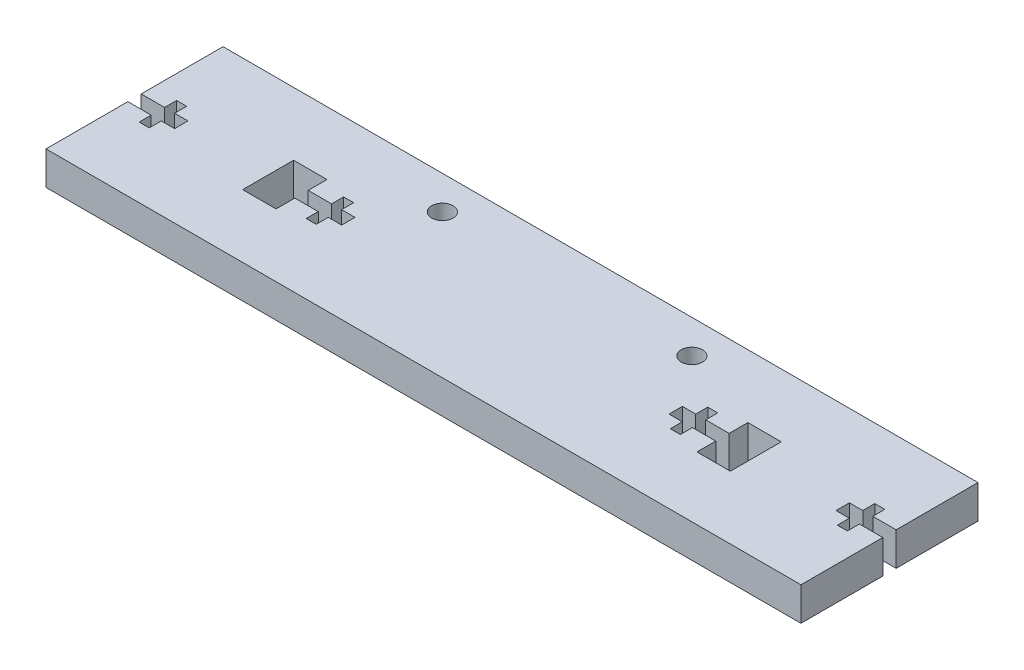
SolidWorks part; units mm, degrees
material "Acrílico (médio-alto impacto)"
ref_plane "Plano frontal" through (0, 0, 0) normal (0, 0, 1) x (1, 0, 0)
ref_plane "Plano superior" through (0, 0, 0) normal (0, 1, 0) x (1, 0, 0)
ref_plane "Plano direito" through (0, 0, 0) normal (1, 0, 0) x (0, 0, -1)
sketch "Esboço1" plane through (0, 0, 0) normal (0, 1, 0) x (1, 0, 0)
  line L1 (-76.7364, -5.6593) -> (36.2636, -5.6593)
  line L2 (-76.7364, -5.6593) -> (-76.7364, -32.1593)
  line L3 (-76.7364, -32.1593) -> (36.2636, -32.1593)
  line L4 (36.2636, -5.6593) -> (36.2636, -32.1593)
extrude "Ressalto-extrusão1" add sketch "Esboço1" along normal blind 5
sketch "Esboço2" plane through (0, 5, 0) normal (0, 1, 0) x (1, 0, 0)
  line L0 (36.2636, -32.1593) -> (36.2636, -5.6593) construction
  line L1 (16.2636, -15.1043) -> (11.2636, -15.1043)
  line L2 (16.2636, -15.1043) -> (16.2636, -22.7243)
  line L3 (16.2636, -22.7243) -> (11.2636, -22.7243)
  line L4 (11.2636, -15.1043) -> (11.2636, -22.7243)
  line L5 (36.2636, -5.6593) -> (-76.7364, -5.6593) construction
  line L9 (-76.7364, -5.6593) -> (-76.7364, -32.1593) construction
  line L10 (-56.7364, -15.1043) -> (-51.7364, -15.1043)
  line L11 (-56.7364, -15.1043) -> (-56.7364, -22.7243)
  line L12 (-56.7364, -22.7243) -> (-51.7364, -22.7243)
  line L13 (-51.7364, -15.1043) -> (-51.7364, -22.7243)
  dimension "D1" = 20
  dimension "D2" = 9.445
  dimension "D3" = 20
extrude "Corte-extrusão1" cut sketch "Esboço2" against normal blind 5
sketch "Esboço3" plane through (0, 5, 0) normal (0, 1, 0) x (1, 0, 0)
  line L0 (-76.7364, -5.6593) -> (-76.7364, -32.1593) construction
  line L1 (-76.7364, -17.9093) -> (-73.2364, -17.9093)
  line L2 (-76.7364, -17.9093) -> (-76.7364, -19.9093)
  line L3 (-76.7364, -19.9093) -> (-73.2364, -19.9093)
  line L4 (-76.7364, -32.1593) -> (36.2636, -32.1593) construction
  line L5 (-73.2364, -19.9093) -> (-73.2364, -21.7093)
  line L6 (-71.7364, -16.1093) -> (-73.2364, -16.1093)
  line L7 (-71.7364, -16.1093) -> (-71.7364, -17.9093)
  line L8 (-71.7364, -21.7093) -> (-73.2364, -21.7093)
  line L9 (-73.2364, -16.1093) -> (-73.2364, -17.9093)
  line L10 (-71.7364, -17.9093) -> (-69.7364, -17.9093)
  line L12 (-71.7364, -19.9093) -> (-69.7364, -19.9093)
  line L13 (-69.7364, -17.9093) -> (-69.7364, -19.9093)
  line L14 (-71.7364, -19.9093) -> (-71.7364, -21.7093)
  line L15 (36.2636, -5.6593) -> (-76.7364, -5.6593) construction
  line L16 (-51.7364, -22.7243) -> (-51.7364, -15.1043) construction
  line L17 (-51.7364, -17.9093) -> (-48.2364, -17.9093)
  line L18 (-51.7364, -17.9093) -> (-51.7364, -19.9093)
  line L19 (-51.7364, -19.9093) -> (-48.2364, -19.9093)
  line L21 (-48.2364, -19.9093) -> (-48.2364, -21.7093)
  line L22 (-46.7364, -16.1093) -> (-48.2364, -16.1093)
  line L23 (-46.7364, -16.1093) -> (-46.7364, -17.9093)
  line L24 (-46.7364, -21.7093) -> (-48.2364, -21.7093)
  line L25 (-48.2364, -16.1093) -> (-48.2364, -17.9093)
  line L26 (-44.7364, -17.9093) -> (-46.7364, -17.9093)
  line L27 (-44.7364, -17.9093) -> (-44.7364, -19.9093)
  line L28 (-44.7364, -19.9093) -> (-46.7364, -19.9093)
  line L30 (-46.7364, -19.9093) -> (-46.7364, -21.7093)
  dimension "D1" = 1.8
  dimension "D2" = 1.8
  dimension "D3" = 1.8
  dimension "D4" = 1.8
  dimension "D5" = 12.25
  dimension "D6" = 12.25
  dimension "D7" = 1.8
  dimension "D8" = 1.8
  dimension "D9" = 1.8
  dimension "D10" = 1.8
  dimension "D11" = 12.25
ref_plane "Plano1" through (-20.2364, 0, 0) normal (-1, 0, 0) x (0, 0, 1)
extrude "Corte-extrusão2" cut sketch "Esboço3" against normal blind 5
mirror "Espelhar1" about plane through (-20.2364, 0, 0) normal (-1, 0, 0) of "Corte-extrusão2"
sketch "Esboço4" plane through (0, 0, 0) normal (0, -1, 0) x (-1, 0, 0)
  line L0 (-36.2636, -17.9093) -> (-36.2636, -5.6593) construction
  line L1 (-36.2636, -5.6593) -> (76.7364, -5.6593) construction
  line L2 (76.7364, -5.6593) -> (76.7364, -17.9093) construction
  circle A0 centre (1.5664, -10.6593) radius 1.6
  circle A1 centre (38.9064, -10.6593) radius 1.6
  dimension "D1" = 37.83
  dimension "D2" = 5
  dimension "D3" = 37.83
  dimension "D4" = 5
extrude "Corte-extrusão3" cut sketch "Esboço4" against normal blind 10
